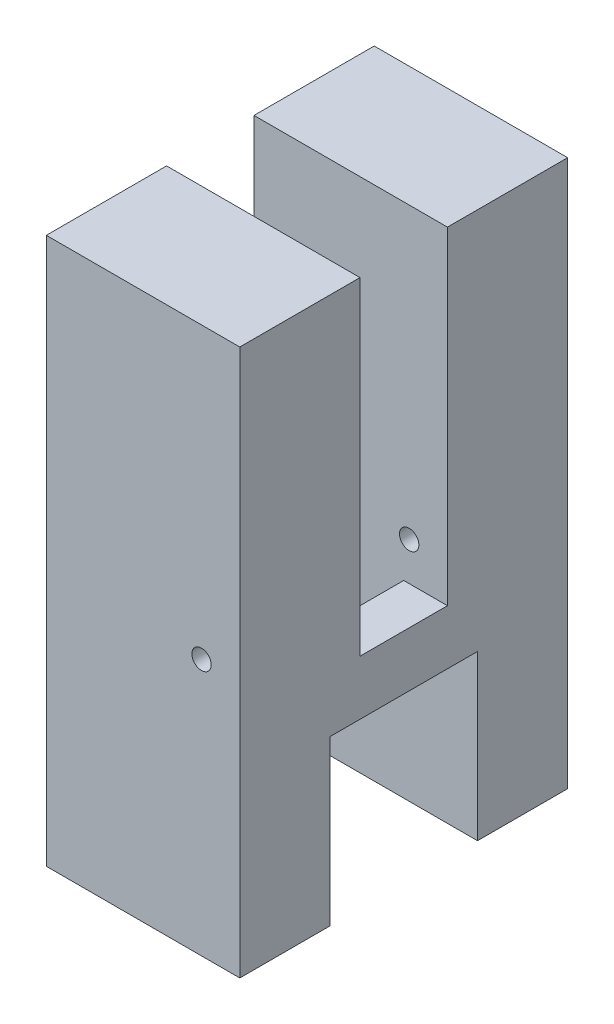
SolidWorks part; units mm, degrees
ref_plane "Front Plane" through (0, 0, 0) normal (0, 0, 1) x (1, 0, 0)
ref_plane "Top Plane" through (0, 0, 0) normal (0, 1, 0) x (1, 0, 0)
ref_plane "Right Plane" through (0, 0, 0) normal (1, 0, 0) x (0, 0, -1)
sketch "Sketch1" plane through (0, 0, 0) normal (0, 1, 0) x (1, 0, 0)
  line L1 (-18.034, 19.05) -> (18.034, 19.05)
  line L2 (-18.034, 19.05) -> (-18.034, -19.05)
  line L3 (-18.034, -19.05) -> (18.034, -19.05)
  line L4 (18.034, 19.05) -> (18.034, -19.05)
  line L5 (-18.034, 19.05) -> (18.034, -19.05) construction
  line L6 (-18.034, -19.05) -> (18.034, 19.05) construction
  point P0 (0, 0)
  dimension "D1" = 38.1
  dimension "D2" = 36.068
extrude "Boss-Extrude1" add sketch "Sketch1" along normal blind 63.5
sketch "Sketch3" plane through (0, 63.5, 0) normal (0, 1, 0) x (1, 0, 0)
  line L0 (18.034, -19.05) -> (18.034, 19.05) construction
  line L1 (-18.034, 5.08) -> (18.034, 5.08)
  line L2 (-18.034, 5.08) -> (-18.034, -5.08)
  line L3 (-18.034, -5.08) -> (18.034, -5.08)
  line L4 (18.034, 5.08) -> (18.034, -5.08)
  line L5 (-18.034, 5.08) -> (18.034, -5.08) construction
  line L6 (-18.034, -5.08) -> (18.034, 5.08) construction
  point P0 (0, 0)
  dimension "D1" = 10.16
extrude "Cut-Extrude1" cut sketch "Sketch3" against normal blind 38.1
sketch "Sketch4" plane through (0, 0, 0) normal (0, -1, 0) x (1, 0, 0)
  line L0 (18.034, 19.05) -> (18.034, -19.05) construction
  line L1 (-18.034, -8.5725) -> (18.034, -8.5725)
  line L2 (-18.034, -8.5725) -> (-18.034, 8.5725)
  line L3 (-18.034, 8.5725) -> (18.034, 8.5725)
  line L4 (18.034, -8.5725) -> (18.034, 8.5725)
  line L5 (-18.034, -8.5725) -> (18.034, 8.5725) construction
  line L6 (-18.034, 8.5725) -> (18.034, -8.5725) construction
  point P0 (0, 0)
  dimension "D1" = 17.145
extrude "Cut-Extrude2" cut sketch "Sketch4" against normal offset from surface (19.05 mm away) 6.35 up to face at (0, 25.4, 0)
sketch "Sketch5" plane through (0, 25.4, 0) normal (0, 1, 0) x (1, 0, 0)
  line L0 (18.034, 5.08) -> (-18.034, 5.08) construction
  line L1 (-0.635, -5.08) -> (0.635, -5.08)
  line L2 (-0.635, -5.08) -> (-0.635, 5.08)
  line L3 (-0.635, 5.08) -> (0.635, 5.08)
  line L4 (0.635, -5.08) -> (0.635, 5.08)
  line L5 (-0.635, -5.08) -> (0.635, 5.08) construction
  line L6 (-0.635, 5.08) -> (0.635, -5.08) construction
  line L7 (-18.034, -8.5725) -> (-18.034, 8.5725) construction
  line L8 (-0.635, 5.08) -> (-18.034, 5.08)
  line L9 (-0.635, 5.08) -> (-0.635, -5.08)
  line L10 (-0.635, -5.08) -> (-18.034, -5.08)
  line L11 (-18.034, 5.08) -> (-18.034, -5.08)
  line L13 (0.635, 5.08) -> (18.034, 5.08)
  line L14 (0.635, 5.08) -> (0.635, -5.08)
  line L15 (0.635, -5.08) -> (18.034, -5.08)
  line L16 (18.034, 5.08) -> (18.034, -5.08)
  point P0 (0, 0)
  line M10 (18.034, -5.08) -> (18.034, 5.08)
  line M11 (18.034, 5.08) -> (-18.034, 5.08)
  line M12 (-18.034, 5.08) -> (-18.034, -5.08)
  line M13 (-18.034, -5.08) -> (18.034, -5.08)
  dimension "D1" = 1.27
extrude "Cut-Extrude3" cut sketch "Sketch5" against normal through all contours L2 M13 M11 M12 | L4 M13 M10 M11
sketch "Sketch6" plane through (0, 0, -5.08) normal (0, 0, 1) x (1, 0, 0)
  line L0 (0.635, 25.4) -> (-0.635, 25.4) construction
  line L1 (0, 0) -> (0, 29.845) construction
  circle A0 centre (0, 29.845) radius 1.125
  dimension "D1" = 2.25
  dimension "D2" = 4.445
extrude "Cut-Extrude4" cut sketch "Sketch6" against normal through all both and the other way through all
sketch "Sketch7" plane through (0, 63.5, 0) normal (0, 1, 0) x (1, 0, 0)
  line L0 (18.034, 19.05) -> (18.034, -19.05)
  line L1 (18.034, 19.05) -> (4.445, 19.05)
  line L2 (18.034, -19.05) -> (4.445, -19.05)
  line L3 (4.445, 19.05) -> (4.445, -19.05)
  line L5 (0.635, -5.08) -> (0.635, 5.08) construction
  dimension "D1" = 3.81
extrude "Cut-Extrude6" cut sketch "Sketch7" against normal through all
sketch "Sketch8" plane through (0.635, 0, 0) normal (1, 0, 0) x (0, 0, -1)
  line L0 (-5.08, 19.05) -> (-5.08, 25.4)
  line L1 (-5.08, 19.05) -> (5.08, 19.05)
  line L2 (-5.08, 25.4) -> (5.08, 25.4)
  line L3 (5.08, 19.05) -> (5.08, 25.4)
extrude "Boss-Extrude2" add sketch "Sketch8" along normal up to surface (3.81 mm away) up to face at (4.445, 27.5167, 10.9008)
